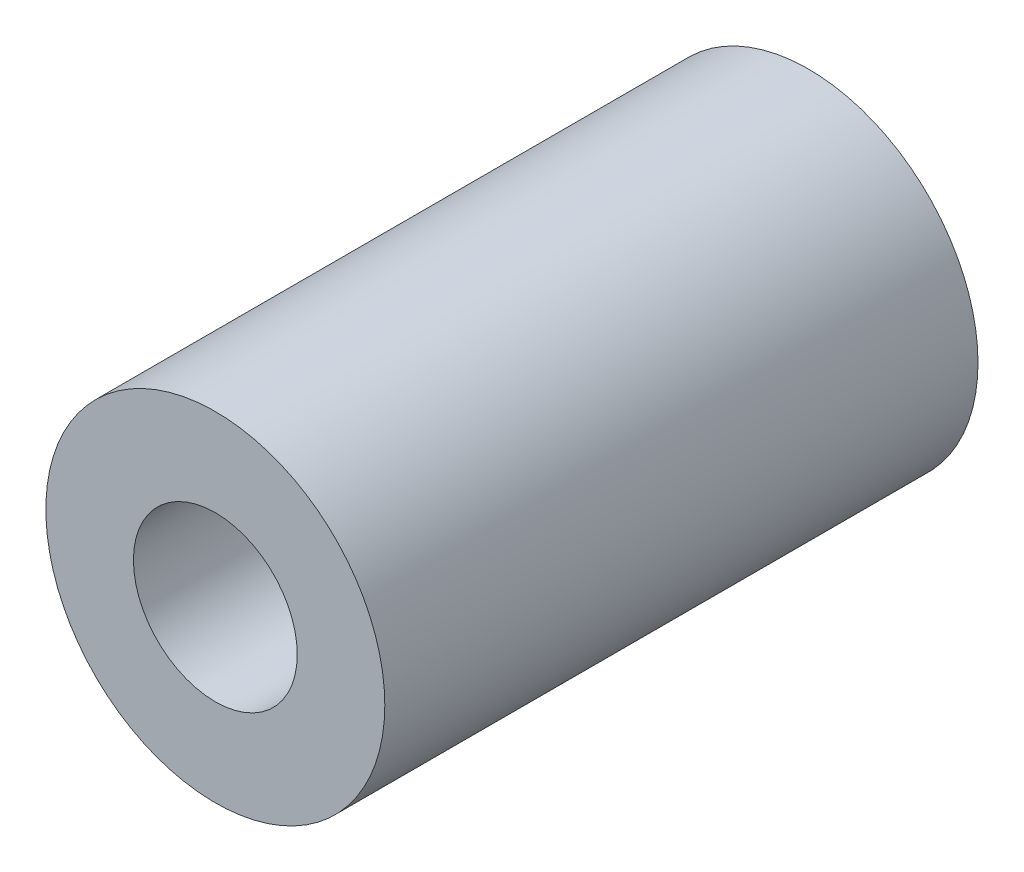
SolidWorks part; units mm, degrees
material "铜"
ref_plane "前视基准面" through (0, 0, 0) normal (0, 0, 1) x (1, 0, 0)
ref_plane "上视基准面" through (0, 0, 0) normal (0, 1, 0) x (1, 0, 0)
ref_plane "右视基准面" through (0, 0, 0) normal (1, 0, 0) x (0, 0, -1)
sketch "草图1" plane through (0, 0, 0) normal (0, 0, 1) x (1, 0, 0)
  circle A0 centre (0, 0) radius 30
  circle A1 centre (0, 0) radius 14.5
  dimension "D1" = 60
  dimension "D2" = 29
extrude "凸台-拉伸1" add sketch "草图1" along normal mid plane 105
